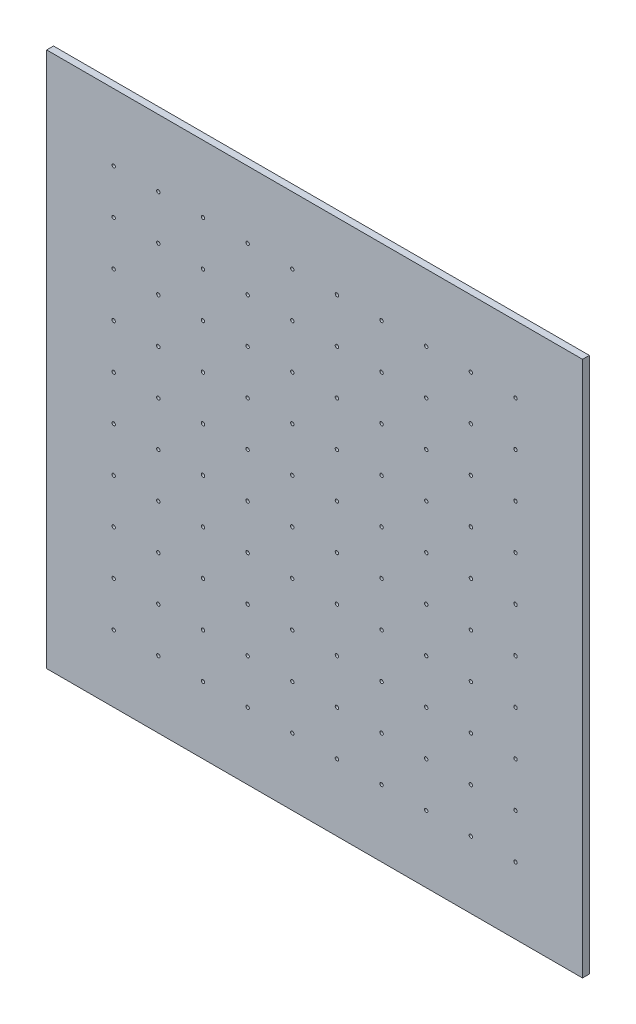
SolidWorks part; units mm, degrees
ref_plane "Front Plane" through (0, 0, 0) normal (0, 0, 1) x (1, 0, 0)
ref_plane "Top Plane" through (0, 0, 0) normal (0, 1, 0) x (1, 0, 0)
ref_plane "Right Plane" through (0, 0, 0) normal (1, 0, 0) x (0, 0, -1)
sketch "Sketch1" plane through (0, 0, 0) normal (0, 0, 1) x (1, 0, 0)
  line L0 (750, -750) -> (-750, 750) construction
  line L1 (-750, 750) -> (750, 750)
  line L2 (-750, 750) -> (-750, -750)
  line L3 (-750, -750) -> (750, -750)
  line L4 (750, 750) -> (750, -750)
  dimension "D1" = 1500
extrude "Boss-Extrude1" add sketch "Sketch1" along normal mid plane 19.05
sketch "Sketch2" plane through (0, 0, 9.525) normal (0, 0, 1) x (1, 0, 0)
  line L0 (750, 750) -> (-750, 750) construction
  line L2 (-562.5, 562.5) -> (-750, 562.5) construction
  line L3 (-562.5, 562.5) -> (-562.5, 750) construction
  line L4 (-562.5, 750) -> (-750, 750) construction
  line L5 (-750, 562.5) -> (-750, 750) construction
  circle A0 centre (-562.5, 562.5) radius 4.7625
  dimension "D2" = 9.525
  dimension "D1" = 187.5
extrude "Cut-Extrude1" cut sketch "Sketch2" against normal through all
pattern_linear "LPattern1" count 10 spacing 125 along (0, -1, 0) count 10 spacing 125 along (1, 0, 0) of "Cut-Extrude1"
